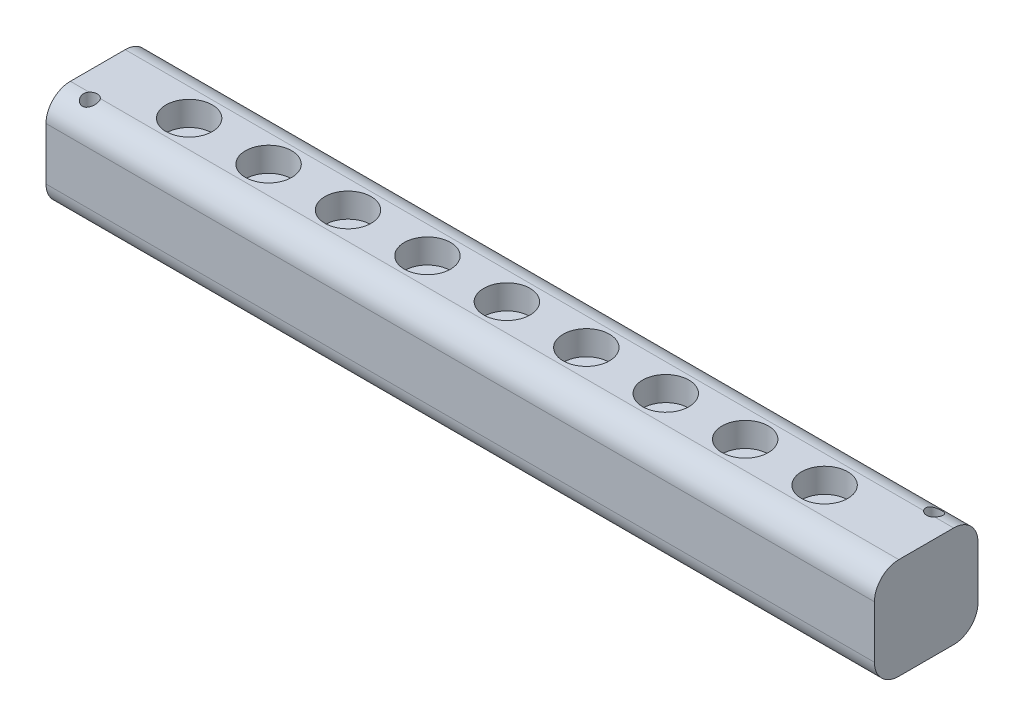
SolidWorks part; units mm, degrees
ref_plane "Front Plane" through (0, 0, 0) normal (0, 0, 1) x (1, 0, 0)
ref_plane "Top Plane" through (0, 0, 0) normal (0, 1, 0) x (1, 0, 0)
ref_plane "Right Plane" through (0, 0, 0) normal (1, 0, 0) x (0, 0, -1)
sketch "Sketch1" plane through (0, 0, 0) normal (0, 1, 0) x (1, 0, 0)
  line L1 (-43.1855, 16.9657) -> (296.8145, 16.9657)
  line L2 (-43.1855, 16.9657) -> (-43.1855, -25.5343)
  line L3 (-43.1855, -25.5343) -> (296.8145, -25.5343)
  line L4 (296.8145, 16.9657) -> (296.8145, -25.5343)
  dimension "D1" = 42.5
  dimension "D2" = 340
extrude "Boss-Extrude1" add sketch "Sketch1" along normal blind 41.5
sketch "Sketch2" plane through (0, 41.5, 0) normal (0, 1, 0) x (1, 0, 0)
  circle A0 centre (-5.6855, -4.2843) radius 9.5
  circle A1 centre (26.9145, -4.2843) radius 9.5
  circle A2 centre (59.5145, -4.2843) radius 9.5
  circle A3 centre (92.1145, -4.2843) radius 9.5
  circle A4 centre (124.7145, -4.2843) radius 9.5
  circle A5 centre (157.3145, -4.2843) radius 9.5
  circle A6 centre (189.9145, -4.2843) radius 9.5
  circle A7 centre (222.5145, -4.2843) radius 9.5
  circle A8 centre (255.1145, -4.2843) radius 9.5
extrude "Cut-Extrude1" cut sketch "Sketch2" against normal blind 10
sketch "Sketch3" plane through (-43.1855, 0, 0) normal (-1, 0, 0) x (0, 0, 1)
  line L0 (-16.9657, 41.5) -> (25.5343, 41.5)
  line L1 (-6.9657, 41.5) -> (15.5343, 41.5)
  line L2 (-16.9657, 31.5) -> (-16.9657, 10)
  line L3 (-6.9657, 0) -> (15.5343, 0)
  line L4 (25.5343, 31.5) -> (25.5343, 10)
  line L5 (25.5343, 41.5) -> (25.5343, 0)
  line L6 (25.5343, 0) -> (-16.9657, 0)
  line L7 (-16.9657, 0) -> (-16.9657, 41.5)
  arc A0 (-16.9657, 10) -> (-6.9657, 0) centre (-6.9657, 10) ccw
  arc A1 (15.5343, 0) -> (25.5343, 10) centre (15.5343, 10) ccw
  arc A2 (15.5343, 41.5) -> (25.5343, 31.5) centre (15.5343, 31.5) cw
  arc A3 (-6.9657, 41.5) -> (-16.9657, 31.5) centre (-6.9657, 31.5) ccw
  point P10 (25.5343, 0)
  point P15 (-16.9657, 41.5)
  line M1 (-16.9657, 0) -> (25.5343, 0)
  line M2 (25.5343, 0) -> (25.5343, 41.5)
  line M3 (25.5343, 41.5) -> (-16.9657, 41.5)
  line M4 (-16.9657, 41.5) -> (-16.9657, 0)
  dimension "D1" = 10
sketch "Sketch4" plane through (0, 41.5, 0) normal (0, 1, 0) x (1, 0, 0)
  circle A1 centre (286.8145, 8.9657) radius 3.05
  circle A3 centre (-33.1855, -17.5343) radius 3.05
extrude "Cut-Extrude3" cut sketch "Sketch4" against normal through all
extrude "Cut-Extrude4" cut sketch "Sketch3" against normal through all contours A3 M3 M4 | A0 M4 M1 | A1 M1 M2 | A2 M3 M2
